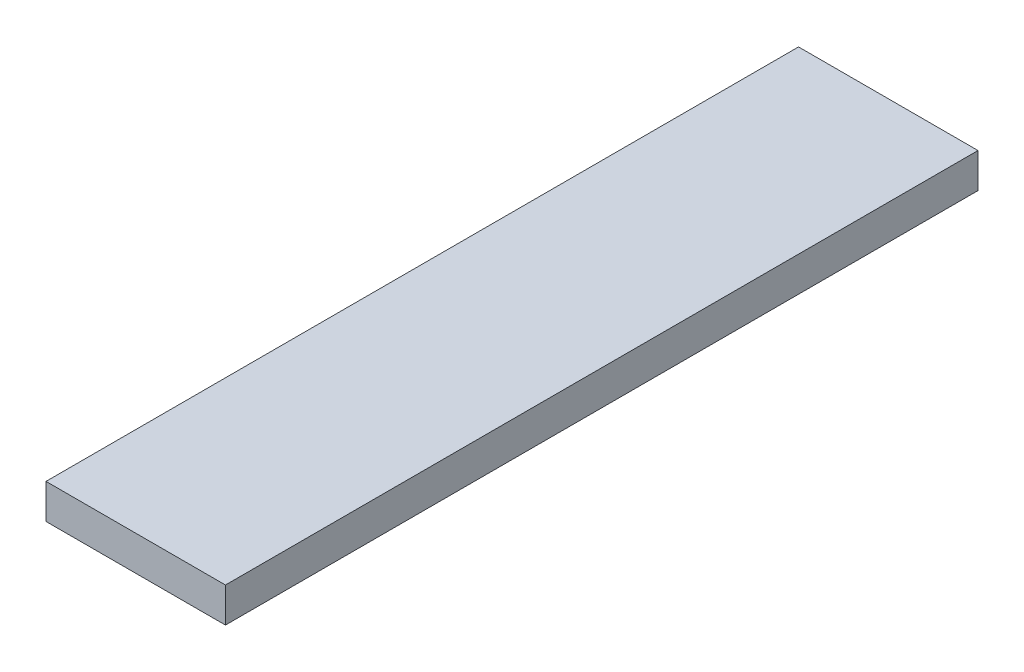
SolidWorks part; units mm, degrees
material "AISI 304"
ref_plane "前视基准面" through (0, 0, 0) normal (0, 0, 1) x (1, 0, 0)
ref_plane "上视基准面" through (0, 0, 0) normal (0, 1, 0) x (1, 0, 0)
ref_plane "右视基准面" through (0, 0, 0) normal (1, 0, 0) x (0, 0, -1)
sketch "Sketch1" plane through (0, 0, 0) normal (0, 1, 0) x (1, 0, 0)
  line L0 (0, 0) -> (0, -130)
  line L1 (0, -130) -> (31, -130)
  line L2 (31, -130) -> (31, 0)
  line L3 (31, 0) -> (0, 0)
  dimension "D1" = 130
  dimension "D2" = 31
extrude "Boss-Extrude1" add sketch "Sketch1" along normal blind 6
